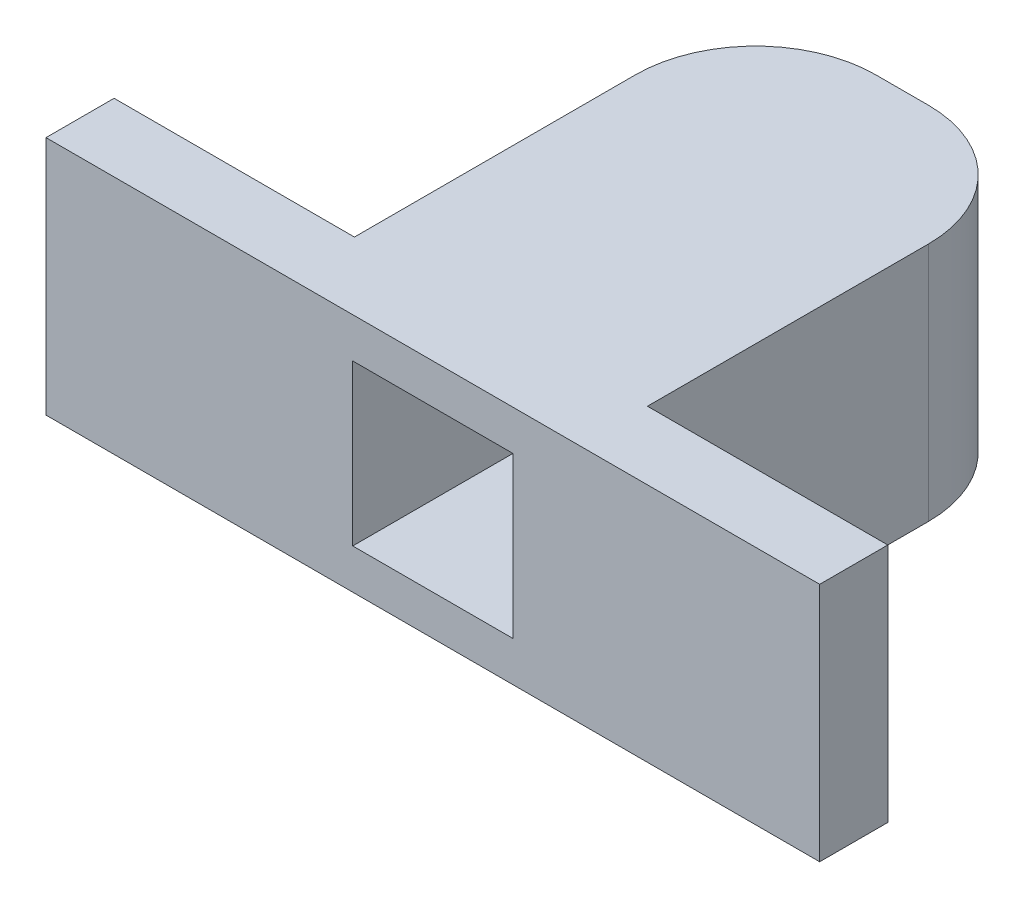
SolidWorks part; units mm, degrees
ref_plane "Front Plane" through (0, 0, 0) normal (0, 0, 1) x (1, 0, 0)
ref_plane "Top Plane" through (0, 0, 0) normal (0, 1, 0) x (1, 0, 0)
ref_plane "Right Plane" through (0, 0, 0) normal (1, 0, 0) x (0, 0, -1)
sketch "Sketch1" plane through (0, 0, 0) normal (0, 1, 0) x (1, 0, 0)
  line L0 (4.2221, 0) -> (4.2221, 0.85)
  line L1 (4.2221, 0.85) -> (7.2221, 0.85)
  line L2 (7.2221, 0.85) -> (7.2221, 4.3577)
  line L3 (8.7221, 5.8577) -> (9.3801, 5.8577)
  line L4 (10.8801, 4.3577) -> (10.8801, 0.85)
  line L5 (10.8801, 0.85) -> (13.8801, 0.85)
  line L6 (13.8801, 0.85) -> (13.8801, 0)
  line L7 (13.8801, 0) -> (4.2221, 0)
  arc A0 (9.3801, 5.8577) -> (10.8801, 4.3577) centre (9.3801, 4.3577) cw
  arc A1 (7.2221, 4.3577) -> (8.7221, 5.8577) centre (8.7221, 4.3577) cw
  dimension "D5" = 1.5
  dimension "D1" = 0.85
  dimension "D2" = 0.85
  dimension "D3" = 3
  dimension "D4" = 3
extrude "Boss-Extrude1" add sketch "Sketch1" along normal blind 3
sketch "Sketch3" plane through (0, 0, 0) normal (0, 0, 1) x (1, 0, 0)
  line L0 (4.2221, 1.5) -> (13.8801, 1.5) construction
  line L1 (4.2221, 3) -> (4.2221, 0) construction
  line L2 (13.8801, 3) -> (13.8801, 0) construction
  line L3 (13.8801, 1.5) -> (9.0511, 1.5) construction
  line L4 (9.0511, 1.5) -> (9.0511, 3) construction
  line L5 (4.2221, 3) -> (13.8801, 3) construction
  line L7 (8.0511, 2.5) -> (10.0511, 2.5)
  line L8 (8.0511, 2.5) -> (8.0511, 0.5)
  line L9 (8.0511, 0.5) -> (10.0511, 0.5)
  line L10 (10.0511, 2.5) -> (10.0511, 0.5)
  line L11 (9.0511, 0.5) -> (9.0511, 2.5) construction
  line L12 (8.0511, 1.5) -> (10.0511, 1.5) construction
  dimension "D1" = 2
  dimension "D2" = 2
extrude "Cut-Extrude1" cut sketch "Sketch3" against normal blind 5
